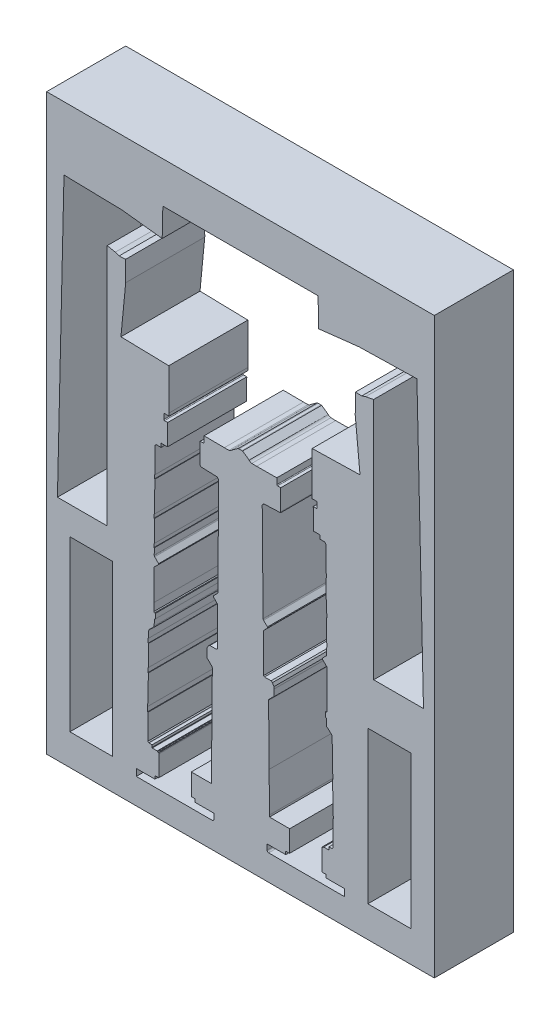
SolidWorks part; units mm, degrees
ref_plane "Front Plane" through (0, 0, 0) normal (0, 0, 1) x (1, 0, 0)
ref_plane "Top Plane" through (0, 0, 0) normal (0, 1, 0) x (1, 0, 0)
ref_plane "Right Plane" through (0, 0, 0) normal (1, 0, 0) x (0, 0, -1)
sketch "Sketch1" plane through (0, 0, 0) normal (0, 0, 1) x (1, 0, 0)
  line L0 (0, 0) -> (0, -65) construction
  line L1 (-18.185, -233.5314) -> (-67.185, -233.5314)
  line L2 (-125, -250) -> (125, -250)
  line L3 (-125, -250) -> (-125, 120)
  line L4 (-125, 120) -> (125, 120)
  line L5 (125, -250) -> (125, 120)
  line L6 (0, 120) -> (0, -250) construction
  line L7 (-125, -65) -> (125, -65) construction
  line L8 (-67.185, -233.5314) -> (-67.185, -229.0314)
  line L9 (-67.185, -229.0314) -> (-55.1733, -229.0314)
  line L10 (-55.114, -229.0314) -> (-58.6495, -229.0314) construction
  line L11 (-55.1733, -229.0314) -> (-55.1733, -227.025)
  line L12 (-55.1733, -227.025) -> (-52.6835, -227.025)
  line L13 (-52.6835, -227.025) -> (-52.685, -213.7137)
  line L14 (-52.685, -213.8961) -> (-52.685, -213.5314) construction
  line L15 (-52.685, -213.7137) -> (-52.6357, -213.0156)
  line L16 (-52.2275, -213.0193) -> (-52.8133, -213.0141) construction
  line L17 (-52.1557, -207.9984) -> (-52.685, -213.5314) construction
  line L18 (-52.6357, -213.0156) -> (-53.0461, -213.0156)
  line L19 (-53.0461, -213.0156) -> (-53.4424, -212.7839)
  line L20 (-53.4424, -212.7839) -> (-53.691, -212.5108)
  line L21 (-53.5177, -212.7148) -> (-55.1273, -210.8188) construction
  line L22 (-53.691, -212.5108) -> (-56.7239, -212.4943)
  line L23 (-56.7239, -212.4943) -> (-56.9568, -212.4943)
  line L24 (-56.9568, -212.4943) -> (-57.0274, -212.2788)
  line L25 (-57.0274, -212.2788) -> (-57.0212, -212.1916)
  line L26 (-57.0212, -212.1916) -> (-57.0083, -210.7546)
  line L27 (-57.0104, -210.9917) -> (-56.9925, -208.9917) construction
  line L28 (-57.0083, -210.7546) -> (-58.8832, -210.7539)
  line L29 (-58.8832, -210.7539) -> (-59.1065, -210.7069)
  line L30 (-59.1065, -210.7069) -> (-59.6782, -210.1015)
  line L31 (-59.6782, -210.1015) -> (-59.5563, -193.9078)
  line L32 (-59.5779, -196.3113) -> (-59.5348, -191.5043) construction
  line L33 (-59.5563, -193.9078) -> (-59.555, -193.7534)
  line L34 (-59.555, -193.7534) -> (-59.8549, -193.7507)
  line L35 (-59.8549, -193.7507) -> (-59.8281, -190.7603)
  line L36 (-59.8281, -190.7603) -> (-59.3578, -171.7762)
  line L37 (-59.3578, -171.7762) -> (-59.6578, -171.7735)
  line L38 (-59.6578, -171.7735) -> (-59.6309, -168.7831)
  line L39 (-59.6309, -168.7831) -> (-59.3309, -168.7858)
  line L40 (-59.3309, -168.7858) -> (-59.2093, -155.2304)
  line L41 (-59.2093, -155.2304) -> (-59.5099, -155.2906)
  line L42 (-59.5099, -155.2906) -> (-59.483, -152.3002)
  line L43 (-59.483, -152.3002) -> (-59.1831, -152.3042)
  line L44 (-59.1831, -152.3042) -> (-59.1443, -147.9864)
  line L45 (-58.8495, -147.2779) -> (-56.2073, -144.6712)
  line L46 (-56.2094, -144.9031) -> (-56.2073, -144.6712) construction
  line L47 (-58.5228, -146.9433) -> (-56.2073, -144.6712) construction
  line L48 (-55.6138, -144.6023) -> (-55.5815, -141.006) construction
  line L49 (-55.6117, -144.3652) -> (-55.6057, -143.7042)
  line L50 (-55.6057, -143.7042) -> (-55.5732, -140.0805)
  line L51 (-54.8668, -139.3727) -> (-54.8668, -136.3236)
  line L52 (-55.3894, -136.319) -> (-53.3896, -136.3369) construction
  line L53 (-54.8668, -136.3236) -> (-55.3894, -136.319)
  line L54 (-55.3894, -136.319) -> (-55.885, -135.8145)
  line L55 (-55.885, -135.8145) -> (-55.8398, -130.7729)
  line L56 (-55.7966, -125.9535) -> (-55.8441, -131.2514) construction
  line L57 (-55.8398, -130.7729) -> (-55.6607, -110.8155)
  line L58 (-55.6607, -110.8155) -> (-52.7817, -107.9877)
  line L59 (-52.7817, -107.9877) -> (-52.7817, -107.4849)
  line L60 (-52.7817, -107.4849) -> (-55.3183, -104.9076)
  line L61 (-55.6013, -104.2015) -> (-55.5641, -100.0599)
  line L62 (-55.2969, -70.2785) -> (-55.6013, -104.2015) construction
  line L63 (-55.5641, -100.0599) -> (-55.8642, -100.0632)
  line L64 (-55.8642, -100.0632) -> (-55.8418, -97.5633)
  line L65 (-55.8418, -97.5633) -> (-55.5418, -97.566)
  line L66 (-55.5418, -97.566) -> (-55.4162, -83.5666)
  line L67 (-55.4162, -83.5666) -> (-55.7162, -83.5639)
  line L68 (-55.7162, -83.5639) -> (-55.6937, -81.064)
  line L69 (-55.6937, -81.064) -> (-55.3937, -81.0667)
  line L70 (-55.3937, -81.0667) -> (-55.2188, -61.5675)
  line L71 (-55.2188, -61.5675) -> (-55.5188, -61.5648)
  line L72 (-55.5188, -61.5648) -> (-55.4963, -59.0649)
  line L73 (-55.4963, -59.0649) -> (-55.1963, -59.0676)
  line L74 (-55.1963, -59.0676) -> (-55.049, -42.6425)
  line L75 (-54.9592, -42.4312) -> (-54.2797, -41.7639)
  line L76 (-54.2797, -41.7639) -> (-51.2037, -41.8353)
  line L77 (-51.1878, -43.599) -> (-51.2058, -41.5991) construction
  line L78 (-51.2037, -41.8353) -> (-51.2037, -39.3892)
  line L79 (-51.2037, -39.3892) -> (-47.0459, -39.3892)
  line L80 (-47.0459, -39.3892) -> (-46.9368, -25.7215)
  line L81 (-46.9368, -25.7215) -> (-48.9487, -25.7215)
  line L82 (-49.4487, -25.2215) -> (-49.4487, -22.2215)
  line L83 (-48.9487, -21.7215) -> (-46.0121, -21.7215)
  line L84 (-46.4487, -21.7215) -> (-26.4487, -21.7215) construction
  line L85 (-46.0121, -21.7215) -> (-45.9982, -19.9215)
  line L86 (-45.9982, -19.9215) -> (-46.2338, 6.3378)
  line L87 (-17.185, -232.5314) -> (-17.185, -229.0314)
  line L88 (-17.185, -229.0314) -> (-29.185, -229.0314)
  line L89 (-113.7968, 79.069) -> (-78.2205, 78.2546)
  line L90 (-29.185, -229.0314) -> (-29.185, -227.5314)
  line L91 (-29.685, -227.0314) -> (-31.6969, -227.0314)
  line L92 (-31.6969, -227.0314) -> (-31.7289, -213.2674)
  line L93 (-31.7289, -213.2674) -> (-27.4066, -213.2674)
  line L94 (-27.4066, -213.2674) -> (-18.7178, -213.2674)
  line L95 (-18.7178, -213.2674) -> (-18.7178, -212.0841)
  line L96 (-18.7178, -212.0841) -> (-18.4905, -186.7531)
  line L97 (-18.4905, -186.7531) -> (-18.1461, -148.3677)
  line L98 (-78.2205, 78.2546) -> (-76.7205, 78.2546)
  line L99 (-18.4325, -147.6495) -> (-21.0387, -144.9613)
  line L100 (-21.0387, -144.9613) -> (-21.6124, -144.5979)
  line L101 (-21.5838, -141.411) -> (-21.6143, -144.8075) construction
  line L102 (-21.6124, -144.5979) -> (-21.5747, -140.3935)
  line L103 (-21.5747, -140.3935) -> (-21.5757, -138.995)
  line L104 (-21.5757, -138.995) -> (-20.604, -137.264)
  line L105 (-20.6597, -137.3739) -> (-20.617, -137.2898) construction
  line L106 (-20.604, -137.264) -> (-19.7356, -136.6389)
  line L107 (-22.0908, -136.6177) -> (-18.391, -136.6509) construction
  line L108 (-19.7356, -136.6389) -> (-15.4498, -136.6773)
  line L109 (-15.4498, -136.6773) -> (-14.8866, -136.1823)
  line L110 (-14.8866, -136.1823) -> (-14.7005, -111.1988)
  line L111 (-14.7005, -111.1988) -> (-17.4901, -108.3043)
  line L112 (-17.4901, -108.3043) -> (-17.4261, -107.7314)
  line L113 (-17.4261, -107.7314) -> (-14.8988, -105.2704)
  line L114 (-14.603, -104.5694) -> (-14.6908, -104.5686) construction
  line L115 (-14.1772, -57.1193) -> (-14.603, -104.5694) construction
  line L116 (-14.603, -104.5694) -> (-14.0349, -41.2568)
  line L117 (-14.0349, -41.2568) -> (-15.0252, -40.1772)
  line L118 (-15.0252, -40.1772) -> (-25.8718, -39.746)
  line L119 (-27.0218, -39.7357) -> (-24.7219, -39.7563) construction
  line L120 (-25.8718, -39.746) -> (-25.9487, -39.2215)
  line L121 (-25.9487, -39.2215) -> (-25.9606, -25.7215)
  line L122 (-25.9606, -25.7215) -> (-23.9487, -25.7215)
  line L123 (-23.4487, -25.2215) -> (-23.4487, -21.4175)
  line L124 (-10.3819, -21.4175) -> (-29.6487, -21.4175) construction
  line L125 (-23.4487, -21.4175) -> (-10.3819, -21.5215)
  line L126 (-5.6102, -20.4582) -> (-1.3757, -17.4633)
  line L127 (-1.3757, -17.4633) -> (-0.8627, -17.4942)
  line L129 (-46.2338, 6.3378) -> (-77.0882, 7.0547)
  line L130 (-77.0882, 7.0547) -> (-74.0165, 38.8078)
  line L131 (-74.0165, 38.8078) -> (-74.1205, 51.7857)
  line L132 (-74.1205, 58.0777) -> (-74.1205, 38.8116) construction
  line L133 (-74.1205, 51.7857) -> (-78.2205, 51.666)
  line L134 (-78.2205, 51.666) -> (-80.7205, 52.5068)
  line L135 (-80.7205, 52.5068) -> (-85.9105, 53.5672)
  line L136 (-85.9105, 53.5672) -> (-85.9105, -103.0044)
  line L137 (-85.9105, -103.0044) -> (-118.0273, -103.0044)
  line L138 (-118.0273, -103.0044) -> (-113.7968, 79.069)
  line L140 (118.0273, -103.0044) -> (113.7968, 79.069)
  line L141 (85.9105, -103.0044) -> (118.0273, -103.0044)
  line L142 (85.9105, 53.5672) -> (85.9105, -103.0044)
  line L143 (80.7205, 52.5068) -> (85.9105, 53.5672)
  line L144 (78.2205, 51.666) -> (80.7205, 52.5068)
  line L145 (74.1205, 51.7857) -> (78.2205, 51.666)
  line L146 (74.0165, 38.8078) -> (74.1205, 51.7857)
  line L147 (77.0882, 7.0547) -> (74.0165, 38.8078)
  line L148 (46.2338, 6.3378) -> (77.0882, 7.0547)
  line L149 (1.3757, -17.4633) -> (0.8627, -17.4942)
  line L150 (5.6102, -20.4582) -> (1.3757, -17.4633)
  line L151 (23.4487, -21.4175) -> (10.3819, -21.5215)
  line L152 (23.4487, -25.2215) -> (23.4487, -21.4175)
  line L153 (25.9606, -25.7215) -> (23.9487, -25.7215)
  line L154 (25.9487, -39.2215) -> (25.9606, -25.7215)
  line L155 (25.8718, -39.746) -> (25.9487, -39.2215)
  line L156 (15.0252, -40.1772) -> (25.8718, -39.746)
  line L157 (14.0349, -41.2568) -> (15.0252, -40.1772)
  line L158 (14.603, -104.5694) -> (14.0349, -41.2568)
  line L159 (17.4261, -107.7314) -> (14.8988, -105.2704)
  line L160 (17.4901, -108.3043) -> (17.4261, -107.7314)
  line L161 (14.7005, -111.1988) -> (17.4901, -108.3043)
  line L162 (14.8866, -136.1823) -> (14.7005, -111.1988)
  line L163 (15.4498, -136.6773) -> (14.8866, -136.1823)
  line L164 (19.7356, -136.6389) -> (15.4498, -136.6773)
  line L165 (20.604, -137.264) -> (19.7356, -136.6389)
  line L166 (21.5757, -138.995) -> (20.604, -137.264)
  line L167 (21.5747, -140.3935) -> (21.5757, -138.995)
  line L168 (21.6124, -144.5979) -> (21.5747, -140.3935)
  line L169 (21.0387, -144.9613) -> (21.6124, -144.5979)
  line L170 (18.4325, -147.6495) -> (21.0387, -144.9613)
  line L171 (18.4905, -186.7531) -> (18.1461, -148.3677)
  line L172 (18.7178, -212.0841) -> (18.4905, -186.7531)
  line L173 (18.7178, -213.2674) -> (18.7178, -212.0841)
  line L174 (27.4066, -213.2674) -> (18.7178, -213.2674)
  line L175 (31.7289, -213.2674) -> (27.4066, -213.2674)
  line L176 (31.6969, -227.0314) -> (31.7289, -213.2674)
  line L177 (29.685, -227.0314) -> (31.6969, -227.0314)
  line L178 (29.185, -229.0314) -> (29.185, -227.5314)
  line L179 (17.185, -229.0314) -> (29.185, -229.0314)
  line L180 (17.185, -232.5314) -> (17.185, -229.0314)
  line L181 (45.9982, -19.9215) -> (46.2338, 6.3378)
  line L182 (46.0121, -21.7215) -> (45.9982, -19.9215)
  line L183 (48.9487, -21.7215) -> (46.0121, -21.7215)
  line L184 (49.4487, -25.2215) -> (49.4487, -22.2215)
  line L185 (46.9368, -25.7215) -> (48.9487, -25.7215)
  line L186 (47.0459, -39.3892) -> (46.9368, -25.7215)
  line L187 (51.2037, -39.3892) -> (47.0459, -39.3892)
  line L188 (51.2037, -41.8353) -> (51.2037, -39.3892)
  line L189 (54.2797, -41.7639) -> (51.2037, -41.8353)
  line L190 (54.9592, -42.4312) -> (54.2797, -41.7639)
  line L191 (55.1963, -59.0676) -> (55.049, -42.6425)
  line L192 (55.4963, -59.0649) -> (55.1963, -59.0676)
  line L193 (55.5188, -61.5648) -> (55.4963, -59.0649)
  line L194 (55.2188, -61.5675) -> (55.5188, -61.5648)
  line L195 (55.3937, -81.0667) -> (55.2188, -61.5675)
  line L196 (55.6937, -81.064) -> (55.3937, -81.0667)
  line L197 (55.7162, -83.5639) -> (55.6937, -81.064)
  line L198 (55.4162, -83.5666) -> (55.7162, -83.5639)
  line L199 (55.5418, -97.566) -> (55.4162, -83.5666)
  line L200 (55.8418, -97.5633) -> (55.5418, -97.566)
  line L201 (55.8642, -100.0632) -> (55.8418, -97.5633)
  line L202 (55.5641, -100.0599) -> (55.8642, -100.0632)
  line L203 (55.6013, -104.2015) -> (55.5641, -100.0599)
  line L204 (52.7817, -107.4849) -> (55.3183, -104.9076)
  line L205 (52.7817, -107.9877) -> (52.7817, -107.4849)
  line L206 (55.6607, -110.8155) -> (52.7817, -107.9877)
  line L207 (55.8398, -130.7729) -> (55.6607, -110.8155)
  line L208 (55.885, -135.8145) -> (55.8398, -130.7729)
  line L209 (55.3894, -136.319) -> (55.885, -135.8145)
  line L210 (54.8668, -136.3236) -> (55.3894, -136.319)
  line L211 (54.8668, -139.3727) -> (54.8668, -136.3236)
  line L212 (55.6057, -143.7042) -> (55.5732, -140.0805)
  line L213 (55.6117, -144.3652) -> (55.6057, -143.7042)
  line L214 (58.8495, -147.2779) -> (56.2073, -144.6712)
  line L215 (59.1831, -152.3042) -> (59.1443, -147.9864)
  line L216 (59.483, -152.3002) -> (59.1831, -152.3042)
  line L217 (59.5099, -155.2906) -> (59.483, -152.3002)
  line L218 (59.2093, -155.2304) -> (59.5099, -155.2906)
  line L219 (59.3309, -168.7858) -> (59.2093, -155.2304)
  line L220 (59.6309, -168.7831) -> (59.3309, -168.7858)
  line L221 (59.6578, -171.7735) -> (59.6309, -168.7831)
  line L222 (59.3578, -171.7762) -> (59.6578, -171.7735)
  line L223 (59.8281, -190.7603) -> (59.3578, -171.7762)
  line L224 (59.8549, -193.7507) -> (59.8281, -190.7603)
  line L225 (59.555, -193.7534) -> (59.8549, -193.7507)
  line L226 (59.5563, -193.9078) -> (59.555, -193.7534)
  line L227 (59.6782, -210.1015) -> (59.5563, -193.9078)
  line L228 (59.1065, -210.7069) -> (59.6782, -210.1015)
  line L229 (58.8832, -210.7539) -> (59.1065, -210.7069)
  line L230 (57.0083, -210.7546) -> (58.8832, -210.7539)
  line L231 (57.0212, -212.1916) -> (57.0083, -210.7546)
  line L232 (57.0274, -212.2788) -> (57.0212, -212.1916)
  line L233 (56.9568, -212.4943) -> (57.0274, -212.2788)
  line L234 (56.7239, -212.4943) -> (56.9568, -212.4943)
  line L235 (53.691, -212.5108) -> (56.7239, -212.4943)
  line L236 (53.4424, -212.7839) -> (53.691, -212.5108)
  line L237 (53.0461, -213.0156) -> (53.4424, -212.7839)
  line L238 (52.6357, -213.0156) -> (53.0461, -213.0156)
  line L239 (52.685, -213.7137) -> (52.6357, -213.0156)
  line L240 (52.6835, -227.025) -> (52.685, -213.7137)
  line L241 (55.1733, -227.025) -> (52.6835, -227.025)
  line L242 (55.1733, -229.0314) -> (55.1733, -227.025)
  line L243 (67.185, -229.0314) -> (55.1733, -229.0314)
  line L244 (67.185, -233.5314) -> (67.185, -229.0314)
  line L245 (18.185, -233.5314) -> (67.185, -233.5314)
  line L246 (-0.8627, -17.4942) -> (0.8627, -17.4942)
  line L247 (-78.2205, 78.2546) -> (-76.7205, 78.2546) construction
  line L248 (-76.7205, 78.2546) -> (-50.4705, 75.2618)
  line L249 (-50.4705, 75.2618) -> (-50.052, 93.5444)
  line L250 (-50.052, 93.5444) -> (50.052, 93.5444)
  line L251 (50.4705, 75.2618) -> (50.052, 93.5444)
  line L252 (76.7205, 78.2546) -> (50.4705, 75.2618)
  line L253 (78.2205, 78.2546) -> (76.7205, 78.2546)
  line L254 (113.7968, 79.069) -> (78.2205, 78.2546)
  arc A0 (-59.1443, -147.9864) -> (-58.8495, -147.2779) centre (-58.1231, -147.9956) cw
  arc A1 (-56.2073, -144.6712) -> (-55.6117, -144.3652) centre (-55.4219, -145.4674) cw
  arc A2 (-55.5732, -140.0805) -> (-54.8668, -139.3727) centre (-54.859, -140.0869) cw
  arc A3 (-52.8354, -107.4137) -> (-52.0197, -107.848) centre (-52.0107, -106.8481) ccw construction
  arc A4 (-55.3183, -104.9076) -> (-55.6013, -104.2015) centre (-54.6158, -104.2163) cw
  arc A5 (-55.049, -42.6425) -> (-54.9592, -42.4312) centre (-54.749, -42.6452) cw
  arc A6 (-48.9487, -25.7215) -> (-49.4487, -25.2215) centre (-48.9487, -25.2215) cw
  arc A7 (-49.4487, -22.2215) -> (-48.9487, -21.7215) centre (-48.9487, -22.2215) cw
  arc A8 (-48.9487, -21.7215) -> (-49.4487, -22.2215) centre (-48.9487, -22.2215) ccw construction
  arc A9 (-18.185, -233.5314) -> (-17.185, -232.5314) centre (-18.185, -232.5314) ccw
  arc A10 (-29.185, -227.5314) -> (-29.685, -227.0314) centre (-29.685, -227.5314) ccw
  arc A11 (-18.1461, -148.3677) -> (-18.4325, -147.6495) centre (-19.1667, -148.3585) ccw
  arc A12 (-21.8167, -139.0593) -> (-21.3958, -138.8223) centre (-21.821, -138.5593) ccw construction
  arc A13 (-18.2495, -108.151) -> (-17.4261, -107.7314) centre (-18.2405, -107.1511) ccw construction
  arc A14 (-14.8988, -105.2704) -> (-14.603, -104.5694) centre (-15.5813, -104.5695) ccw
  arc A15 (-23.9487, -25.7215) -> (-23.4487, -25.2215) centre (-23.9487, -25.2215) ccw construction
  arc A16 (-23.9487, -25.7215) -> (-23.4487, -25.2215) centre (-23.9487, -25.2215) ccw
  arc A17 (-10.3819, -21.5215) -> (-7.3366, -21.4175) centre (-10.0938, 14.6833) ccw
  arc A18 (-7.3366, -21.4175) -> (-5.6102, -20.4582) centre (-7.5166, -19.0603) ccw
  arc A19 (7.3366, -21.4175) -> (5.6102, -20.4582) centre (7.5166, -19.0603) cw
  arc A20 (10.3819, -21.5215) -> (7.3366, -21.4175) centre (10.0938, 14.6833) cw
  arc A21 (23.9487, -25.7215) -> (23.4487, -25.2215) centre (23.9487, -25.2215) cw
  arc A22 (14.8988, -105.2704) -> (14.603, -104.5694) centre (15.5813, -104.5695) cw
  arc A23 (18.1461, -148.3677) -> (18.4325, -147.6495) centre (19.1667, -148.3585) cw
  arc A24 (29.185, -227.5314) -> (29.685, -227.0314) centre (29.685, -227.5314) cw
  arc A25 (18.185, -233.5314) -> (17.185, -232.5314) centre (18.185, -232.5314) cw
  arc A26 (49.4487, -22.2215) -> (48.9487, -21.7215) centre (48.9487, -22.2215) ccw
  arc A27 (48.9487, -25.7215) -> (49.4487, -25.2215) centre (48.9487, -25.2215) ccw
  arc A28 (55.049, -42.6425) -> (54.9592, -42.4312) centre (54.749, -42.6452) ccw
  arc A29 (55.3183, -104.9076) -> (55.6013, -104.2015) centre (54.6158, -104.2163) ccw
  arc A30 (55.5732, -140.0805) -> (54.8668, -139.3727) centre (54.859, -140.0869) ccw
  arc A31 (56.2073, -144.6712) -> (55.6117, -144.3652) centre (55.4219, -145.4674) ccw
  arc A32 (59.1443, -147.9864) -> (58.8495, -147.2779) centre (58.1231, -147.9956) ccw
  ellipse E0 centre (-21.736, -145.6462) end of major axis (-22.4522, -144.9171) minor radius 0.9775 (-20.9117, -145.1177) -> (-21.7271, -144.6472) ccw construction
  ellipse E1 centre (-17.327, -107.235) end of major axis (-17.1103, -106.7248) minor radius 0.2296 (-17.6297, -107.5323) -> (-17.4261, -107.7314) ccw construction
  spline S0 degree 3 poles (-52.6768, -226.6569) (-52.6768, -226.6583) (-52.6768, -226.6609) (-52.6769, -226.6647) (-52.677, -226.6677) (-52.677, -226.6708) (-52.6771, -226.6734) (-52.6771, -226.6769) (-52.6772, -226.6802) (-52.6773, -226.6836) (-52.6773, -226.6879) (-52.6774, -226.6923) (-52.6776, -226.7008) (-52.6777, -226.7088) (-52.6779, -226.7165) (-52.678, -226.7214) (-52.6781, -226.727) (-52.6782, -226.7342) (-52.6783, -226.7398) (-52.6784, -226.744) (-52.6784, -226.7463) (-52.6785, -226.7492) (-52.6785, -226.7514) (-52.6786, -226.7541) (-52.6786, -226.7562) (-52.6787, -226.7595) (-52.6788, -226.7628) (-52.6788, -226.7673) (-52.6789, -226.7714) (-52.679, -226.7772) (-52.6792, -226.7837) (-52.6793, -226.7921) (-52.6794, -226.7988) (-52.6796, -226.8053) (-52.6797, -226.8098) (-52.6797, -226.8143) (-52.6798, -226.8176) (-52.6799, -226.8206) (-52.6799, -226.8229) (-52.6799, -226.8254) (-52.68, -226.8279) (-52.68, -226.8294) (-52.68, -226.8306) (-52.6801, -226.8319) (-52.6801, -226.8335) (-52.6801, -226.8354) (-52.6802, -226.8382) (-52.6803, -226.8425) (-52.6804, -226.8482) (-52.6805, -226.8551) (-52.6806, -226.862) (-52.6808, -226.8681) (-52.6808, -226.8723) (-52.6809, -226.8759) (-52.681, -226.879) (-52.681, -226.8826) (-52.6811, -226.8859) (-52.6812, -226.8908) (-52.6813, -226.8964) (-52.6814, -226.9034) (-52.6815, -226.9094) (-52.6816, -226.9141) (-52.6817, -226.9169) (-52.6817, -226.919) (-52.6817, -226.9212) (-52.6818, -226.924) (-52.6818, -226.9267) (-52.6819, -226.9298) (-52.6819, -226.9331) (-52.682, -226.9382) (-52.6821, -226.9445) (-52.6823, -226.9519) (-52.6824, -226.9587) (-52.6825, -226.966) (-52.6827, -226.9745) (-52.6828, -226.982) (-52.6829, -226.9896) (-52.683, -226.9945) (-52.6831, -226.999) (-52.6831, -227.0017) (-52.6832, -227.0055) (-52.6832, -227.01) (-52.6833, -227.0144) (-52.6834, -227.0189) (-52.6834, -227.0234) (-52.6835, -227.0275) (-52.6836, -227.0303) (-52.6836, -227.0352) (-52.6837, -227.0401) (-52.6838, -227.0451) (-52.6839, -227.0511) (-52.684, -227.0602) (-52.6842, -227.0724) (-52.6843, -227.0824) (-52.6844, -227.0915) (-52.6845, -227.0995) (-52.6846, -227.1085) (-52.6847, -227.1179) (-52.6849, -227.128) (-52.685, -227.1394) (-52.6851, -227.1515) (-52.6852, -227.1627) (-52.6853, -227.1726) (-52.6854, -227.1797) (-52.6854, -227.1854) (-52.6855, -227.1893) (-52.6855, -227.196) (-52.6856, -227.206) (-52.6858, -227.2319) (-52.6859, -227.2607) (-52.686, -227.2961) (-52.6861, -227.3152) (-52.6861, -227.3285) (-52.6861, -227.3319) (-52.6861, -227.3341) (-52.6861, -227.3364) (-52.6861, -227.3391) (-52.6861, -227.3436) (-52.6861, -227.3482) (-52.6861, -227.3547) (-52.6861, -227.3605) (-52.686, -227.3678) (-52.686, -227.3741) (-52.686, -227.3804) (-52.686, -227.3856) (-52.686, -227.3901) (-52.686, -227.3958) (-52.6859, -227.4012) (-52.6859, -227.4076) (-52.6859, -227.4125) (-52.6859, -227.4214) (-52.6858, -227.4341) (-52.6857, -227.4508) (-52.6855, -227.471) (-52.6854, -227.4884) (-52.6853, -227.5019) (-52.6852, -227.5116) (-52.6851, -227.518) (-52.6851, -227.5228) knots 0 0 0 0 0.006052 0.01128 0.015913 0.018642 0.02446 0.027305 0.034027 0.038216 0.041549 0.052181 0.057247 0.077676 0.086006 0.090004 0.098545 0.109382 0.120448 0.122329 0.127055 0.129781 0.134378 0.136288 0.141615 0.143264 0.150007 0.155786 0.162066 0.166904 0.180365 0.189281 0.201884 0.208475 0.216399 0.219936 0.227746 0.229915 0.232422 0.237452 0.239786 0.241816 0.243523 0.24496 0.248102 0.250454 0.252938 0.259539 0.268346 0.276225 0.288038 0.296739 0.301094 0.305195 0.311414 0.314182 0.319884 0.324279 0.334543 0.342245 0.35288 0.35868 0.361197 0.364038 0.367125 0.370024 0.375336 0.378776 0.382328 0.388207 0.398982 0.407527 0.417831 0.425856 0.43634 0.451492 0.455345 0.465811 0.470613 0.472818 0.476453 0.48538 0.490186 0.493716 0.502303 0.5076 0.509633 0.513031 0.525818 0.528517 0.532032 0.548426 0.562788 0.577583 0.585363 0.596525 0.606752 0.617888 0.630425 0.642809 0.658624 0.672452 0.681804 0.692175 0.696734 0.700945 0.705318 0.71906 0.733893 0.789186 0.808677 0.837574 0.842611 0.844872 0.846682 0.848657 0.850923 0.853944 0.860512 0.863101 0.870744 0.875612 0.881733 0.88678 0.891344 0.894671 0.897836 0.905505 0.907715 0.913319 0.91738 0.929122 0.943658 0.956715 0.97689 0.984595 0.988743 1 1 1 1 construction
  spline S1 degree 3 poles (-52.9859, -212.9975) (-53.1865, -212.9604) (-53.3748, -212.8603) (-53.5177, -212.7148) knots 0 0 0 0 1 1 1 1 construction
  spline S2 degree 3 poles (-5.5414, -20.3969) (-5.6317, -20.4828) (-5.7319, -20.5558) (-5.8395, -20.6142) knots 0 0 0 0 1 1 1 1 construction
  spline S3 degree 3 poles (-88.9633, 54.1598) (-87.1146, 53.6618) (-85.2, 53.4085) (-83.2853, 53.4085) knots 0 0 0 0 1 1 1 1 construction
  point P267 (0, 79.069)
  point P442 (0, 93.5444)
  dimension "D1" = 370
  dimension "D2" = 250
  dimension "D3" = 250
extrude "Boss-Extrude1" add sketch "Sketch1" along normal blind 51
sketch "Sketch2" plane through (0, 0, 51) normal (0, 0, 1) x (1, 0, 0)
  line L0 (125, -250) -> (125, 120) construction
  line L1 (-82.6644, -230) -> (-110, -230)
  line L2 (-82.6644, -230) -> (-82.6644, -121.0568)
  line L3 (-82.6644, -121.0568) -> (-110, -121.0568)
  line L4 (-110, -230) -> (-110, -121.0568)
  line L5 (-96.3322, -121.0568) -> (-96.3322, -230) construction
  line L6 (-82.6644, -175.5284) -> (-110, -175.5284) construction
  line L7 (110, -230) -> (82.1477, -230)
  line L8 (110, -230) -> (110, -131.9065)
  line L9 (110, -131.9065) -> (82.1477, -131.9065)
  line L10 (82.1477, -230) -> (82.1477, -131.9065)
  line L11 (96.0739, -131.9065) -> (96.0739, -230) construction
  line L12 (110, -180.9532) -> (82.1477, -180.9532) construction
  line L13 (-125, 120) -> (-125, -250) construction
  line L14 (-125, -250) -> (125, -250) construction
  point P0 (-96.3322, -175.5284)
  point P7 (96.0739, -180.9532)
  point P14 (-82.6644, -121.0568)
  point P15 (82.1477, -131.9065)
  dimension "D1" = 15
  dimension "D2" = 15
  dimension "D3" = 20
  dimension "D4" = 20
extrude "Cut-Extrude1" cut sketch "Sketch2" against normal through all
